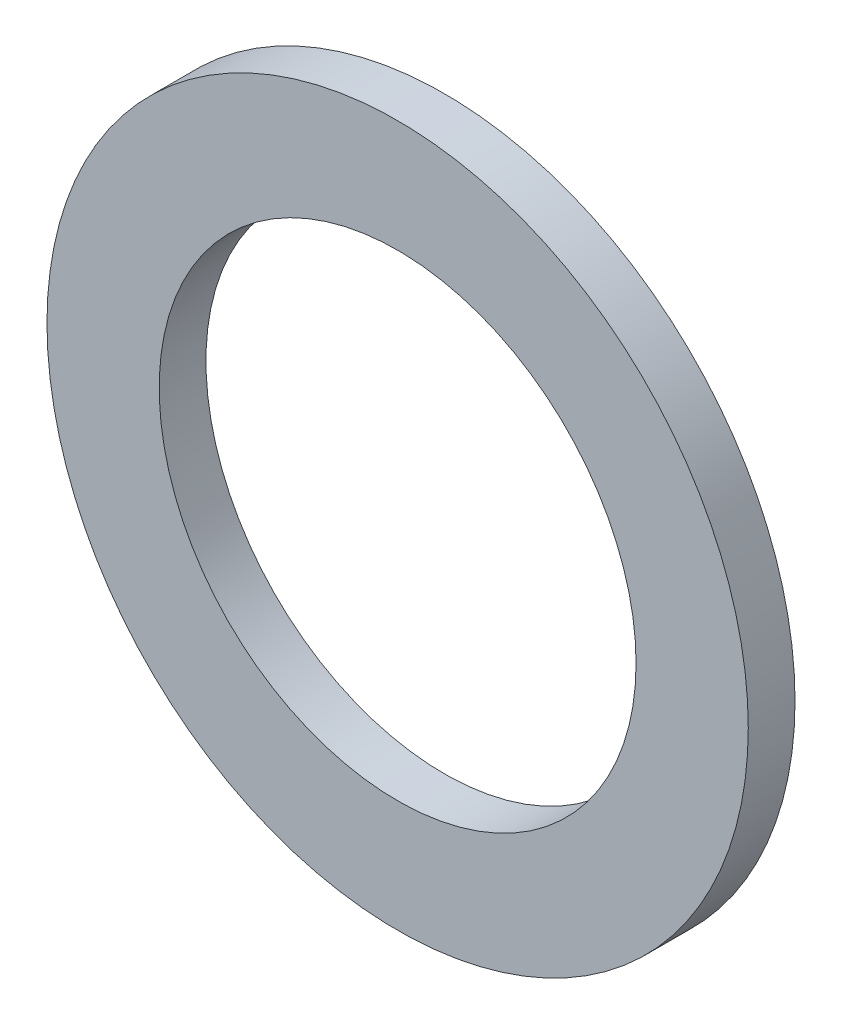
SolidWorks part; units mm, degrees
material "Epoxy, renforcé"
ref_plane "Plan de face" through (0, 0, 0) normal (0, 0, 1) x (1, 0, 0)
ref_plane "Plan de dessus" through (0, 0, 0) normal (0, 1, 0) x (1, 0, 0)
ref_plane "Plan de droite" through (0, 0, 0) normal (1, 0, 0) x (0, 0, -1)
sketch "Esquisse1" plane through (0, 0, 0) normal (0, 0, 1) x (1, 0, 0)
  circle A0 centre (0, 0) radius 5.1
  circle A1 centre (0, 0) radius 7.5
  dimension "D1" = 10.2
  dimension "D2" = 15
extrude "Boss.-Extru.1" add sketch "Esquisse1" along normal blind 1
